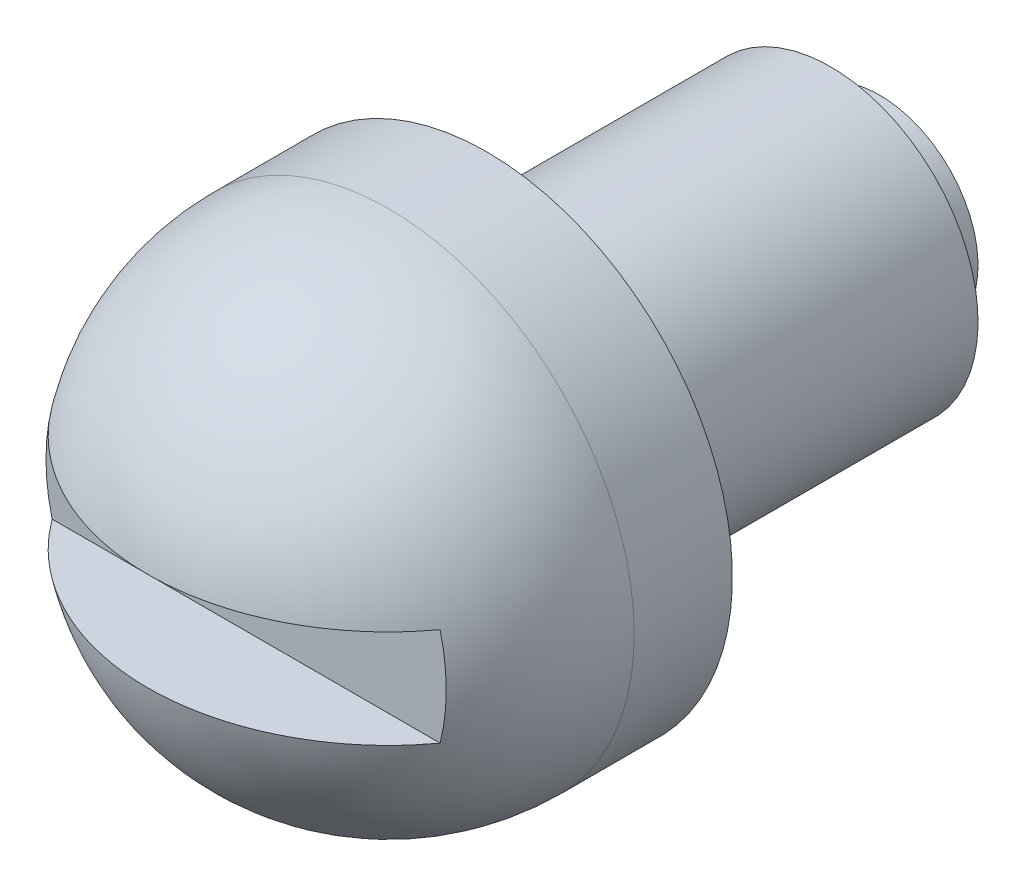
SolidWorks part; units mm, degrees
material "Alloy Steel"
ref_plane "Front Plane" through (0, 0, 0) normal (0, 0, 1) x (1, 0, 0)
ref_plane "Top Plane" through (0, 0, 0) normal (0, 1, 0) x (1, 0, 0)
ref_plane "Right Plane" through (0, 0, 0) normal (1, 0, 0) x (0, 0, -1)
sketch "Sketch1" plane through (0, 0, 0) normal (1, 0, 0) x (0, 0, -1)
  line L0 (-24, 0) -> (24, 0) construction
  line L1 (2.2741, 0) -> (2.2741, 2)
  line L2 (2.2741, 2) -> (1.2741, 2)
  line L3 (1.2741, 2) -> (1.2741, 3)
  line L4 (1.2741, 3) -> (-5.7259, 3)
  line L5 (-5.7259, 3) -> (-5.7259, 5)
  line L6 (-5.7259, 5) -> (-7.7259, 5)
  line L7 (2.2741, 0) -> (-12.7259, 0)
  line L14 (-14.827, 0) -> (-10.6249, 0) construction
  arc A1 (-7.7259, 5) -> (-12.7259, 0) centre (-7.7259, 0) ccw
  point P4 (0, 0)
  dimension "D7" = 10
  dimension "D1" = 7
  dimension "D2" = 1
  dimension "D3" = 2
  dimension "D4" = 6
  dimension "D5" = 10
  dimension "D6" = 2
revolve "Revolve1" add sketch "Sketch1" angle 360 about L0
sketch "Sketch2" plane through (0, 0, 0) normal (1, 0, 0) x (0, 0, -1)
  line L1 (-14.827, 1) -> (-10.6249, 1)
  line L2 (-14.827, 1) -> (-14.827, -1)
  line L3 (-14.827, -1) -> (-10.6249, -1)
  line L4 (-10.6249, 1) -> (-10.6249, -1)
  line L5 (-12.7259, -1) -> (-12.7259, 1) construction
  line L6 (-14.827, 0) -> (-10.6249, 0) construction
  arc A0 (-7.7259, 5) -> (-7.7259, -5) centre (-7.7259, 0) ccw construction
  point P0 (-12.7259, 0)
  dimension "D1" = 2
  dimension "D2" = 10.6249
extrude "Cut-Extrude1" cut sketch "Sketch2" against normal through all both and the other way through all
